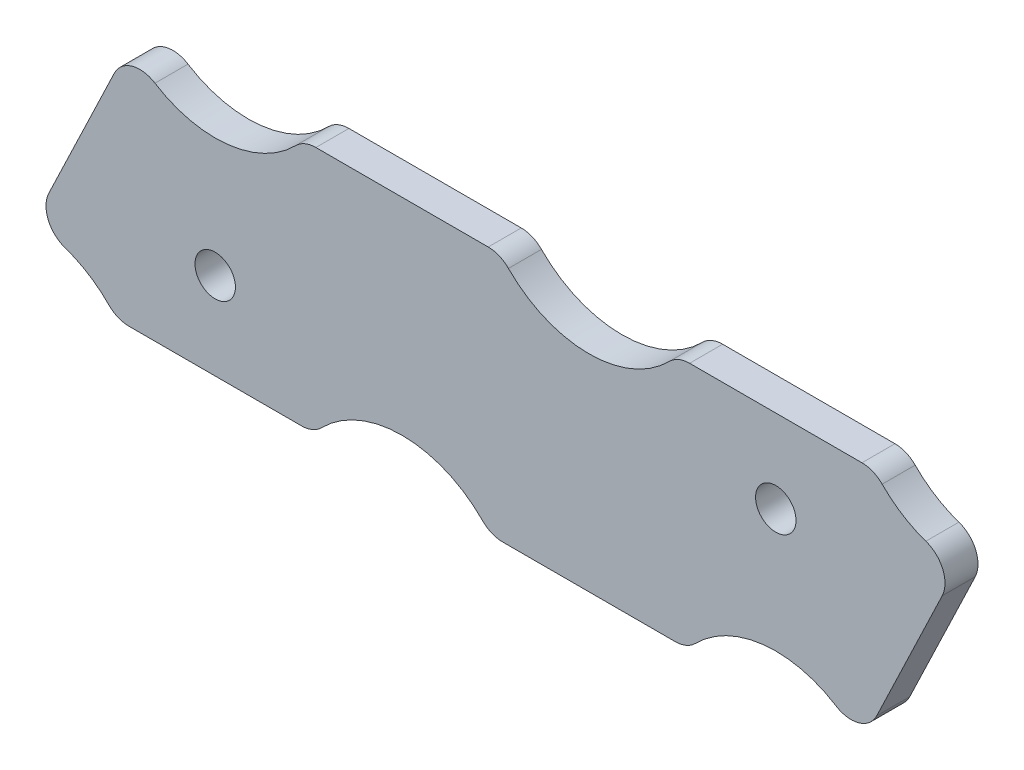
SolidWorks part; units mm, degrees
material "3003-H14"
ref_plane "X-Y Datum" through (0, 0, 0) normal (0, 0, 1) x (1, 0, 0)
ref_plane "X-Z Datum" through (0, 0, 0) normal (0, 1, 0) x (1, 0, 0)
ref_plane "Y-Z Datum" through (0, 0, 0) normal (1, 0, 0) x (0, 0, -1)
sketch "Sketch3" plane through (0, 0, 0) normal (0, 0, 1) x (1, 0, 0)
  line L0 (10.775, 10.775) -> (22.275, 34.775) construction
  line L1 (0, 0) -> (156.4633, 0) construction
  line L2 (0, 0) -> (0, 56.3098) construction
  line L3 (0, 56.3098) -> (156.4633, 56.3098) construction
  line L4 (156.4633, 0) -> (156.4633, 56.3098) construction
  line L5 (33.775, 10.775) -> (45.275, 34.775) construction
  line L6 (56.775, 10.775) -> (68.275, 34.775) construction
  line L7 (16.525, 22.775) -> (62.525, 22.775) construction
  line L8 (33.775, 10.775) -> (22.275, 34.775) construction
  line L9 (45.275, 34.775) -> (56.775, 10.775) construction
  line L10 (10.775, 10.775) -> (33.775, 10.775) construction
  line L11 (56.775, 10.775) -> (33.775, 10.775) construction
  line L12 (22.275, 34.775) -> (45.275, 34.775) construction
  line L13 (68.275, 34.775) -> (45.275, 34.775) construction
  line L14 (22.275, 34.775) -> (22.275, 10.775) construction
  line L15 (45.275, 10.775) -> (45.275, 34.775) construction
  line L16 (33.775, 10.775) -> (33.775, 34.775) construction
  line L17 (56.775, 34.775) -> (56.775, 10.775) construction
  line L18 (13.4804, 9.4786) -> (24.9804, 33.4786)
  line L19 (36.4804, 9.4786) -> (47.9804, 33.4786)
  line L20 (59.4804, 9.4786) -> (70.9804, 33.4786)
  line L21 (8.0696, 12.0714) -> (19.5696, 36.0714)
  line L22 (31.0696, 12.0714) -> (42.5696, 36.0714)
  line L23 (54.0696, 12.0714) -> (65.5696, 36.0714)
  line L24 (17.8152, 18.525) -> (57.1619, 18.525)
  line L25 (21.8881, 27.025) -> (61.2348, 27.025)
  line L26 (16.525, 27.025) -> (62.525, 27.025) construction
  line L27 (16.525, 18.525) -> (62.525, 18.525) construction
  line L28 (16.0692, 14.8813) -> (28.4808, 14.8813)
  line L29 (39.9808, 30.6687) -> (27.5692, 30.6687)
  line L48 (56.775, 10.775) -> (68.275, 10.775) construction
  line L49 (68.275, 10.775) -> (68.275, 34.775) construction
  line L50 (62.9808, 30.6687) -> (50.5692, 30.6687)
  line L51 (39.0692, 14.8813) -> (51.4808, 14.8813)
  circle A0 centre (10.775, 10.775) radius 10.775 construction
  circle A1 centre (33.775, 10.775) radius 10.775 construction
  circle A2 centre (22.275, 34.775) radius 10.775 construction
  circle A3 centre (45.275, 34.775) radius 10.775 construction
  circle A4 centre (68.275, 34.775) radius 10.775 construction
  circle A5 centre (56.775, 10.775) radius 10.775 construction
  circle A6 centre (10.775, 10.775) radius 4.7 construction
  circle A7 centre (33.775, 10.775) radius 4.7 construction
  circle A8 centre (56.775, 10.775) radius 4.7 construction
  circle A9 centre (68.275, 34.775) radius 4.7 construction
  circle A10 centre (45.275, 34.775) radius 4.7 construction
  circle A11 centre (22.275, 34.775) radius 4.7 construction
  circle A12 centre (22.275, 34.775) radius 6.7
  circle A13 centre (10.775, 10.775) radius 6.7
  circle A14 centre (33.775, 10.775) radius 6.7
  circle A15 centre (45.275, 34.775) radius 6.7
  circle A16 centre (68.275, 34.775) radius 6.7
  circle A17 centre (56.775, 10.775) radius 6.7
  circle A18 centre (125.775, 10.775) radius 10.775 construction
  circle A19 centre (102.775, 10.775) radius 10.775 construction
  circle A20 centre (79.775, 10.775) radius 10.775 construction
  circle A21 centre (91.275, 34.775) radius 10.775 construction
  circle A22 centre (114.275, 34.775) radius 10.775 construction
  circle A23 centre (137.275, 34.775) radius 10.775 construction
  dimension "D1" = 21.55
  dimension "D9" = 9.4
  dimension "D2" = 23
  dimension "D3" = 24
  dimension "D4" = 11.5
  dimension "D6" = 23
  dimension "D8" = 23
  dimension "D10" = 3
  dimension "D11" = 3
  dimension "D12" = 4.25
  dimension "D13" = 4.25
  dimension "D14" = 2
  dimension "D5" = 6
  dimension "D7" = 5
extrude "Boss-Extrude1" add sketch "Sketch3" along normal blind 2.032
ref_plane "Plane1" through (68.275, 0, 0) normal (1, 0, 0) x (0, 0, -1)
fillet "Fillet1" radius 2 12 edges at (62.9808, 30.6687, 1.016) (50.5692, 30.6687, 1.016) (39.9808, 30.6687, 1.016) (27.5692, 30.6687, 1.016) (16.0692, 14.8813, 1.016) (28.4808, 14.8813, 1.016) (39.0692, 14.8813, 1.016) (51.4808, 14.8813, 1.016) (68.3917, 28.076, 1.016) (62.0692, 14.8813, 1.016) (10.6583, 17.474, 1.016) (16.9808, 30.6687, 1.016)
sketch "Sketch4" plane through (0, 0, 2.032) normal (0, 0, 1) x (1, 0, 0)
  circle A0 centre (22.275, 20.4921) radius 1.2446
  circle A1 centre (56.775, 25.307) radius 1.2446
  point P0 (56.775, 25.307)
  point P1 (22.275, 20.4921)
  dimension "D1" = 2.4892
extrude "Cut-Extrude1" cut sketch "Sketch4" against normal through all
sketch "Sketch5" [suppressed] plane through (0, 0, 2.032) normal (0, 0, 1) x (1, 0, 0)
  line L0 (13.8196, 24.0714) -> (66.4728, 24.0714)
  line L1 (11.8041, 19.8652) -> (15.835, 28.2776) construction
  line L2 (63.215, 17.2724) -> (67.2459, 25.6848) construction
  line L3 (65.2304, 21.4786) -> (12.5772, 21.4786)
  line L5 (40.1462, 24.0714) -> (40.1462, 21.4786)
  line L6 (38.9038, 21.4786) -> (38.9038, 24.0714)
  line L7 (38.9038, 22.775) -> (40.1462, 22.775)
  line L9 (16.025, 27.275) -> (63.025, 27.275)
  line L10 (16.025, 27.275) -> (16.025, 18.275)
  line L11 (16.025, 18.275) -> (63.025, 18.275)
  line L12 (63.025, 27.275) -> (63.025, 18.275)
  line L13 (16.025, 27.275) -> (63.025, 18.275) construction
  line L14 (16.025, 18.275) -> (63.025, 27.275) construction
  point P11 (40.1462, 24.0714)
  point P15 (39.525, 22.775)
  dimension "D1" = 47
  dimension "D2" = 9
sketch "Sketch6" plane through (0, 0, 2.032) normal (0, 0, 1) x (1, 0, 0)
  line L0 (16.0641, 28.1678) -> (12.0331, 19.7554)
  line L1 (16.9721, 15.1353) -> (27.5779, 15.1353)
  line L2 (39.9721, 15.1353) -> (50.5779, 15.1353)
  line L3 (62.9859, 17.3822) -> (67.0169, 25.7946)
  line L4 (62.0779, 30.4147) -> (51.4721, 30.4147)
  line L5 (39.0779, 30.4147) -> (28.4721, 30.4147)
  line L6 (62.0779, 30.6687) -> (51.4721, 30.6687)
  line L7 (39.0779, 30.6687) -> (28.4721, 30.6687)
  line L8 (15.835, 28.2776) -> (11.8041, 19.8652)
  line L9 (16.9721, 14.8813) -> (27.5779, 14.8813)
  line L10 (39.9721, 14.8813) -> (50.5779, 14.8813)
  line L11 (63.215, 17.2724) -> (67.2459, 25.6848)
  line L12 (62.0779, 30.6687) -> (51.4721, 30.6687)
  line L13 (39.0779, 30.6687) -> (28.4721, 30.6687)
  line L14 (15.835, 28.2776) -> (11.8041, 19.8652)
  line L15 (16.9721, 14.8813) -> (27.5779, 14.8813)
  line L16 (39.9721, 14.8813) -> (50.5779, 14.8813)
  line L17 (63.215, 17.2724) -> (67.2459, 25.6848)
  arc A0 (12.0331, 19.7554) -> (13.0392, 17.3501) centre (13.6077, 19.0009) ccw
  arc A1 (15.7284, 15.6558) -> (13.0392, 17.3501) centre (10.775, 10.775) ccw
  arc A2 (15.7284, 15.6558) -> (16.9721, 15.1353) centre (16.9721, 16.8813) ccw
  arc A3 (27.5779, 15.1353) -> (28.8216, 15.6558) centre (27.5779, 16.8813) ccw
  arc A4 (38.7284, 15.6558) -> (28.8216, 15.6558) centre (33.775, 10.775) ccw
  arc A5 (38.7284, 15.6558) -> (39.9721, 15.1353) centre (39.9721, 16.8813) ccw
  arc A6 (50.5779, 15.1353) -> (51.8216, 15.6558) centre (50.5779, 16.8813) ccw
  arc A7 (60.4809, 16.6593) -> (51.8216, 15.6558) centre (56.775, 10.775) ccw
  arc A8 (60.4809, 16.6593) -> (62.9859, 17.3822) centre (61.4113, 18.1367) ccw
  arc A9 (67.0169, 25.7946) -> (66.0108, 28.1999) centre (65.4423, 26.5491) ccw
  arc A10 (63.3216, 29.8942) -> (66.0108, 28.1999) centre (68.275, 34.775) ccw
  arc A11 (63.3216, 29.8942) -> (62.0779, 30.4147) centre (62.0779, 28.6687) ccw
  arc A12 (51.4721, 30.4147) -> (50.2284, 29.8942) centre (51.4721, 28.6687) ccw
  arc A13 (40.3216, 29.8942) -> (50.2284, 29.8942) centre (45.275, 34.775) ccw
  arc A14 (40.3216, 29.8942) -> (39.0779, 30.4147) centre (39.0779, 28.6687) ccw
  arc A15 (28.4721, 30.4147) -> (27.2284, 29.8942) centre (28.4721, 28.6687) ccw
  arc A16 (18.5691, 28.8907) -> (27.2284, 29.8942) centre (22.275, 34.775) ccw
  arc A17 (18.5691, 28.8907) -> (16.0641, 28.1678) centre (17.6387, 27.4133) ccw
  arc A18 (63.5026, 30.0725) -> (66.0935, 28.4401) centre (68.275, 34.775) ccw
  arc A19 (63.5026, 30.0725) -> (62.0779, 30.6687) centre (62.0779, 28.6687) ccw
  arc A20 (51.4721, 30.6687) -> (50.0474, 30.0725) centre (51.4721, 28.6687) ccw
  arc A21 (40.5026, 30.0725) -> (50.0474, 30.0725) centre (45.275, 34.775) ccw
  arc A22 (40.5026, 30.0725) -> (39.0779, 30.6687) centre (39.0779, 28.6687) ccw
  arc A23 (28.4721, 30.6687) -> (27.0474, 30.0725) centre (28.4721, 28.6687) ccw
  arc A24 (18.7045, 29.1057) -> (27.0474, 30.0725) centre (22.275, 34.775) ccw
  arc A25 (18.7045, 29.1057) -> (15.835, 28.2776) centre (17.6387, 27.4133) ccw
  arc A26 (11.8041, 19.8652) -> (12.9565, 17.1099) centre (13.6077, 19.0009) ccw
  arc A27 (15.5474, 15.4775) -> (12.9565, 17.1099) centre (10.775, 10.775) ccw
  arc A28 (15.5474, 15.4775) -> (16.9721, 14.8813) centre (16.9721, 16.8813) ccw
  arc A29 (27.5779, 14.8813) -> (29.0026, 15.4775) centre (27.5779, 16.8813) ccw
  arc A30 (38.5474, 15.4775) -> (29.0026, 15.4775) centre (33.775, 10.775) ccw
  arc A31 (38.5474, 15.4775) -> (39.9721, 14.8813) centre (39.9721, 16.8813) ccw
  arc A32 (50.5779, 14.8813) -> (52.0026, 15.4775) centre (50.5779, 16.8813) ccw
  arc A33 (60.3455, 16.4443) -> (52.0026, 15.4775) centre (56.775, 10.775) ccw
  arc A34 (60.3455, 16.4443) -> (63.215, 17.2724) centre (61.4113, 18.1367) ccw
  arc A35 (67.2459, 25.6848) -> (66.0935, 28.4401) centre (65.4423, 26.5491) ccw
  arc A36 (63.5026, 30.0725) -> (66.0935, 28.4401) centre (68.275, 34.775) ccw
  arc A37 (63.5026, 30.0725) -> (62.0779, 30.6687) centre (62.0779, 28.6687) ccw
  arc A38 (51.4721, 30.6687) -> (50.0474, 30.0725) centre (51.4721, 28.6687) ccw
  arc A39 (40.5026, 30.0725) -> (50.0474, 30.0725) centre (45.275, 34.775) ccw
  arc A40 (40.5026, 30.0725) -> (39.0779, 30.6687) centre (39.0779, 28.6687) ccw
  arc A41 (28.4721, 30.6687) -> (27.0474, 30.0725) centre (28.4721, 28.6687) ccw
  arc A42 (18.7045, 29.1057) -> (27.0474, 30.0725) centre (22.275, 34.775) ccw
  arc A43 (18.7045, 29.1057) -> (15.835, 28.2776) centre (17.6387, 27.4133) ccw
  arc A44 (11.8041, 19.8652) -> (12.9565, 17.1099) centre (13.6077, 19.0009) ccw
  arc A45 (15.5474, 15.4775) -> (12.9565, 17.1099) centre (10.775, 10.775) ccw
  arc A46 (15.5474, 15.4775) -> (16.9721, 14.8813) centre (16.9721, 16.8813) ccw
  arc A47 (27.5779, 14.8813) -> (29.0026, 15.4775) centre (27.5779, 16.8813) ccw
  arc A48 (38.5474, 15.4775) -> (29.0026, 15.4775) centre (33.775, 10.775) ccw
  arc A49 (38.5474, 15.4775) -> (39.9721, 14.8813) centre (39.9721, 16.8813) ccw
  arc A50 (50.5779, 14.8813) -> (52.0026, 15.4775) centre (50.5779, 16.8813) ccw
  arc A51 (60.3455, 16.4443) -> (52.0026, 15.4775) centre (56.775, 10.775) ccw
  arc A52 (60.3455, 16.4443) -> (63.215, 17.2724) centre (61.4113, 18.1367) ccw
  arc A53 (67.2459, 25.6848) -> (66.0935, 28.4401) centre (65.4423, 26.5491) ccw
  dimension "D1" = 0
  dimension "D2" = 0.254
extrude "Cut-Extrude2" cut sketch "Sketch6" against normal through all
